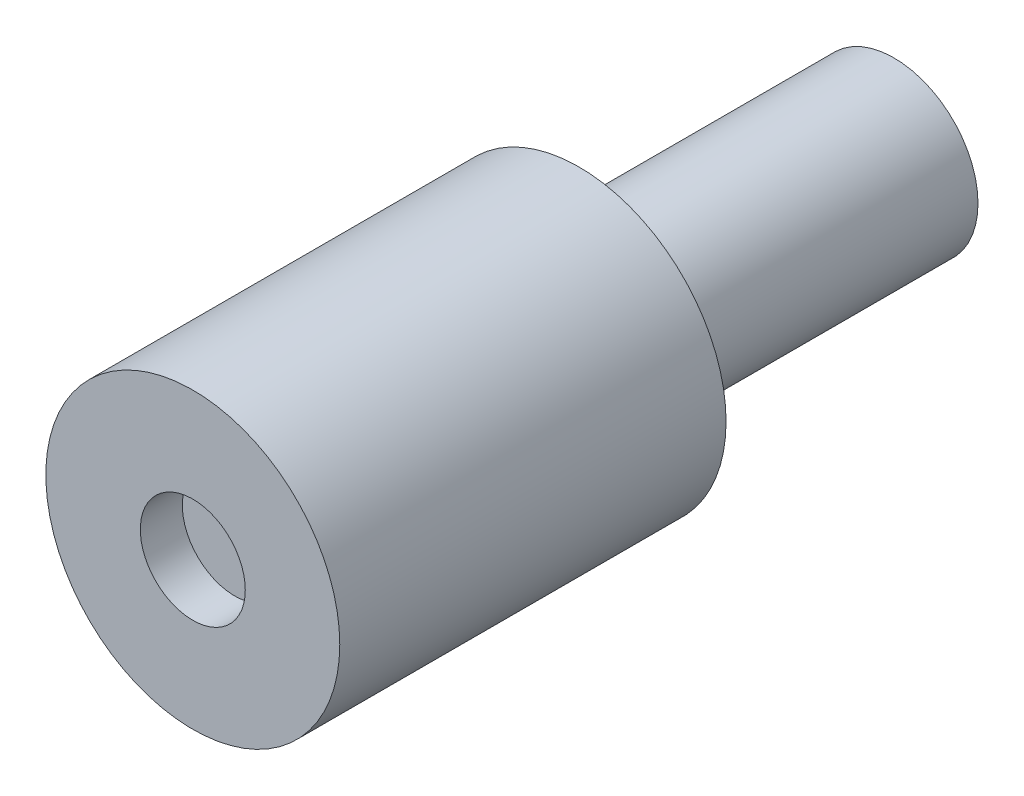
SolidWorks part; units mm, degrees
ref_plane "Front Plane" through (0, 0, 0) normal (0, 0, 1) x (1, 0, 0)
ref_plane "Top Plane" through (0, 0, 0) normal (0, 1, 0) x (1, 0, 0)
ref_plane "Right Plane" through (0, 0, 0) normal (1, 0, 0) x (0, 0, -1)
sketch "Sketch1" plane through (0, 0, 0) normal (0, 0, 1) x (1, 0, 0)
  circle A0 centre (0, 0) radius 4
  dimension "D1" = 8
extrude "Boss-Extrude1" add sketch "Sketch1" along normal blind 15
sketch "Sketch3" plane through (0, 0, 15) normal (0, 0, 1) x (1, 0, 0)
  circle A0 centre (0, 0) radius 7
  dimension "D1" = 14
extrude "Boss-Extrude3" add sketch "Sketch3" along normal blind 18.4
sketch "Sketch5" plane through (0, 0, 33.4) normal (0, 0, 1) x (1, 0, 0)
  circle A0 centre (0, 0) radius 2.5
  dimension "D1" = 5
extrude "Cut-Extrude2" cut sketch "Sketch5" against normal blind 2
